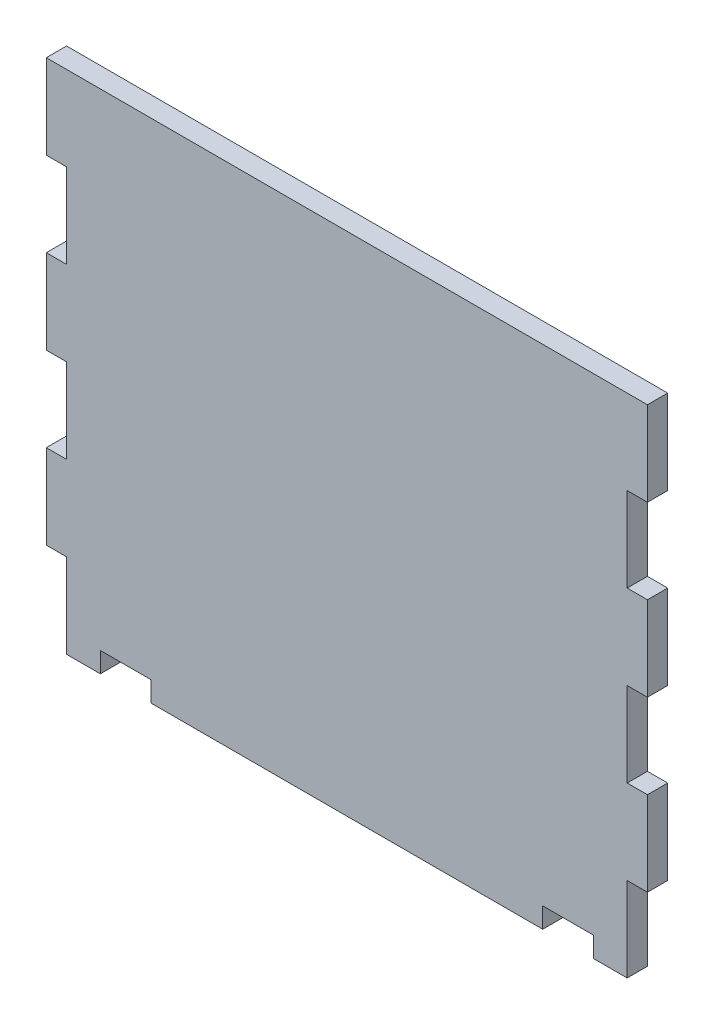
SolidWorks part; units mm, degrees
ref_plane "Front" through (0, 0, 0) normal (0, 0, 1) x (1, 0, 0)
ref_plane "Top" through (0, 0, 0) normal (0, 1, 0) x (1, 0, 0)
ref_plane "Right" through (0, 0, 0) normal (1, 0, 0) x (0, 0, -1)
sketch "Sketch1" plane through (0, 0, 0) normal (0, 0, 1) x (1, 0, 0)
  line L1 (0, 0) -> (-178, 0)
  line L2 (0, 0) -> (0, 150)
  line L3 (0, 150) -> (-178, 150)
  line L4 (-178, 0) -> (-178, 150)
  dimension "D1" = 150
  dimension "D2" = 178
extrude "Boss-Extrude1" add sketch "Sketch1" along normal blind 6
sketch "Sketch2" plane through (0, 0, 6) normal (0, 0, 1) x (1, 0, 0)
  line L0 (-178, 150) -> (-178, 0) construction
  line L1 (-178, 125) -> (-172, 125)
  line L2 (-178, 125) -> (-178, 100)
  line L3 (-178, 100) -> (-172, 100)
  line L4 (-172, 125) -> (-172, 100)
  line L5 (0, 150) -> (-178, 150) construction
  dimension "D1" = 25
  dimension "D2" = 25
  dimension "D3" = 6
extrude "Cut-Extrude1" cut sketch "Sketch2" against normal blind 6
pattern_linear "LPattern1" count 3 spacing 50 along (0, -1, 0) count 2 spacing 172 along (1, 0, 0) of "Cut-Extrude1"
sketch "Sketch3" plane through (0, 0, 6) normal (0, 0, 1) x (1, 0, 0)
  line L0 (-172, 0) -> (-6, 0) construction
  line L1 (-16, 0) -> (-31, 0)
  line L2 (-16, 0) -> (-16, 6)
  line L3 (-16, 6) -> (-31, 6)
  line L4 (-31, 0) -> (-31, 6)
  line L5 (-89, 150) -> (-89, 0) construction
  line L6 (-6, 25) -> (-6, 0) construction
  line L7 (0, 150) -> (-178, 150) construction
  line L8 (-147, 0) -> (-147, 6)
  line L9 (-162, 6) -> (-147, 6)
  line L10 (-162, 0) -> (-162, 6)
  line L11 (-162, 0) -> (-147, 0)
  dimension "D1" = 15
  dimension "D2" = 10
  dimension "D3" = 6
extrude "Cut-Extrude2" cut sketch "Sketch3" against normal through all
